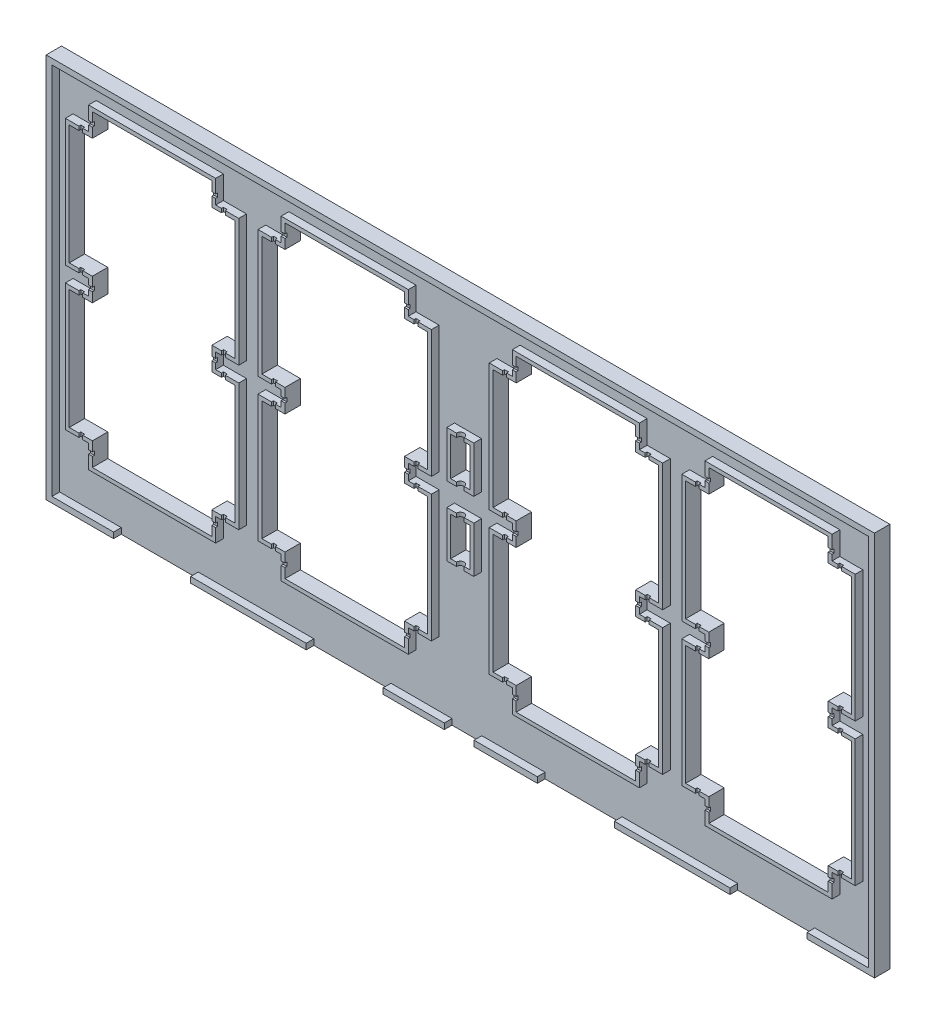
SolidWorks part; units mm, degrees
ref_plane "Спереди" through (0, 0, 0) normal (0, 0, 1) x (1, 0, 0)
ref_plane "Сверху" through (0, 0, 0) normal (0, 1, 0) x (1, 0, 0)
ref_plane "Справа" through (0, 0, 0) normal (1, 0, 0) x (0, 0, -1)
other "Configuration Table"
sketch "Эскиз1" plane through (0, 0, 0) normal (0, 0, 1) x (1, 0, 0)
  line L0 (0, 0) -> (210, 0)
  line L1 (210, 0) -> (210, 100)
  line L2 (210, 100) -> (0, 100)
  line L3 (0, 100) -> (0, 0)
  dimension "D1" = 210
  dimension "D2" = 100
extrude "Бобышка-Вытянуть1" add sketch "Эскиз1" along normal blind 2
sketch "Эскиз2" plane through (0, 0, 2) normal (0, 0, 1) x (1, 0, 0)
  line L4 (3.5, 56.2516) -> (9.5, 56.2516)
  line L5 (40.5, 87.2516) -> (46.5, 87.2516)
  line L6 (9.5, 56.2516) -> (9.5, 50.2516)
  line L7 (9.5, 93.2516) -> (9.5, 87.2516)
  line L9 (40.5, 87.2516) -> (40.5, 93.2516)
  line L10 (40.5, 93.2516) -> (9.5, 93.2516)
  line L11 (53.5, 56.2516) -> (59.5, 56.2516)
  line L12 (9.5, 19.2516) -> (9.5, 13.2516)
  line L13 (9.5, 13.2516) -> (40.5, 13.2516)
  line L14 (40.5, 13.2516) -> (40.5, 19.2516)
  line L16 (90.5, 87.2516) -> (96.5, 87.2516)
  line L20 (40.5, 56.2516) -> (40.5, 50.2516)
  line L21 (59.5, 56.2516) -> (59.5, 50.2516)
  line L22 (59.5, 93.2516) -> (59.5, 87.2516)
  line L23 (25, 93.2516) -> (25, 13.3713) construction
  line L24 (25, 56.2516) -> (25, 33.3628) construction
  line L25 (3.5, 50.2516) -> (3.5, 19.2516)
  line L26 (3.5, 19.2516) -> (9.5, 19.2516)
  line L28 (9.5, 50.2516) -> (3.5, 50.2516)
  line L30 (40.5, 56.2516) -> (46.5, 56.2516)
  line L31 (46.5, 56.2516) -> (46.5, 87.2516)
  line L33 (3.5, 87.2516) -> (3.5, 56.2516)
  line L36 (9.5, 87.2516) -> (3.5, 87.2516)
  line L38 (40.5, 19.2516) -> (46.5, 19.2516)
  line L39 (46.5, 19.2516) -> (46.5, 50.2516)
  line L40 (46.5, 50.2516) -> (40.5, 50.2516)
  line L41 (25, 19.2516) -> (25, 10.047) construction
  line L42 (6.5, 87.2516) -> (6.5, 54.1946) construction
  line L43 (0, 100) -> (0, 0) construction
  line L45 (90.5, 87.2516) -> (90.5, 93.2516)
  line L46 (90.5, 93.2516) -> (59.5, 93.2516)
  line L47 (59.5, 19.2516) -> (59.5, 13.2516)
  line L48 (59.5, 13.2516) -> (90.5, 13.2516)
  line L49 (90.5, 13.2516) -> (90.5, 19.2516)
  line L53 (90.5, 56.2516) -> (90.5, 50.2516)
  line L54 (53.5, 50.2516) -> (53.5, 19.2516)
  line L55 (53.5, 19.2516) -> (59.5, 19.2516)
  line L57 (59.5, 50.2516) -> (53.5, 50.2516)
  line L59 (90.5, 56.2516) -> (96.5, 56.2516)
  line L60 (96.5, 56.2516) -> (96.5, 87.2516)
  line L61 (53.5, 87.2516) -> (53.5, 56.2516)
  line L63 (59.5, 87.2516) -> (53.5, 87.2516)
  line L65 (90.5, 19.2516) -> (96.5, 19.2516)
  line L66 (96.5, 19.2516) -> (96.5, 50.2516)
  line L67 (96.5, 50.2516) -> (90.5, 50.2516)
  line L68 (75, 93.2516) -> (75, 13.3713) construction
  line L69 (75, 56.2516) -> (75, 33.3628) construction
  line L70 (75, 19.2516) -> (75, 10.047) construction
  line L71 (56.5, 87.2516) -> (56.5, 54.1946) construction
  line L72 (3.5, 56.2516) -> (9.5, 56.2516) construction
  line L73 (113.5, 56.2516) -> (119.5, 56.2516)
  line L74 (150.5, 87.2516) -> (156.5, 87.2516)
  line L75 (119.5, 56.2516) -> (119.5, 50.2516)
  line L76 (119.5, 93.2516) -> (119.5, 87.2516)
  line L78 (150.5, 87.2516) -> (150.5, 93.2516)
  line L79 (150.5, 93.2516) -> (119.5, 93.2516)
  line L80 (119.5, 19.2516) -> (119.5, 13.2516)
  line L81 (119.5, 13.2516) -> (150.5, 13.2516)
  line L82 (150.5, 13.2516) -> (150.5, 19.2516)
  line L86 (150.5, 56.2516) -> (150.5, 50.2516)
  line L87 (113.5, 50.2516) -> (113.5, 19.2516)
  line L88 (113.5, 19.2516) -> (119.5, 19.2516)
  line L90 (119.5, 50.2516) -> (113.5, 50.2516)
  line L92 (150.5, 56.2516) -> (156.5, 56.2516)
  line L93 (156.5, 56.2516) -> (156.5, 87.2516)
  line L94 (113.5, 87.2516) -> (113.5, 56.2516)
  line L96 (119.5, 87.2516) -> (113.5, 87.2516)
  line L98 (150.5, 19.2516) -> (156.5, 19.2516)
  line L99 (156.5, 19.2516) -> (156.5, 50.2516)
  line L100 (156.5, 50.2516) -> (150.5, 50.2516)
  line L101 (135, 93.2516) -> (135, 13.3713) construction
  line L102 (135, 56.2516) -> (135, 33.3628) construction
  line L103 (135, 19.2516) -> (135, 10.047) construction
  line L104 (116.5, 87.2516) -> (116.5, 54.1946) construction
  line L105 (90.5, 56.2516) -> (96.5, 56.2516) construction
  line L106 (53.5, 56.2516) -> (59.5, 56.2516) construction
  line L107 (163.5, 56.2516) -> (169.5, 56.2516)
  line L108 (200.5, 87.2516) -> (206.5, 87.2516)
  line L109 (169.5, 56.2516) -> (169.5, 50.2516)
  line L110 (169.5, 93.2516) -> (169.5, 87.2516)
  line L112 (200.5, 87.2516) -> (200.5, 93.2516)
  line L113 (200.5, 93.2516) -> (169.5, 93.2516)
  line L114 (169.5, 19.2516) -> (169.5, 13.2516)
  line L115 (169.5, 13.2516) -> (200.5, 13.2516)
  line L116 (200.5, 13.2516) -> (200.5, 19.2516)
  line L120 (200.5, 56.2516) -> (200.5, 50.2516)
  line L121 (163.5, 50.2516) -> (163.5, 19.2516)
  line L122 (163.5, 19.2516) -> (169.5, 19.2516)
  line L124 (169.5, 50.2516) -> (163.5, 50.2516)
  line L126 (200.5, 56.2516) -> (206.5, 56.2516)
  line L127 (206.5, 56.2516) -> (206.5, 87.2516)
  line L128 (163.5, 87.2516) -> (163.5, 56.2516)
  line L130 (169.5, 87.2516) -> (163.5, 87.2516)
  line L132 (200.5, 19.2516) -> (206.5, 19.2516)
  line L133 (206.5, 19.2516) -> (206.5, 50.2516)
  line L134 (206.5, 50.2516) -> (200.5, 50.2516)
  line L135 (185, 93.2516) -> (185, 13.3713) construction
  line L136 (185, 56.2516) -> (185, 33.3628) construction
  line L137 (185, 19.2516) -> (185, 10.047) construction
  line L138 (166.5, 87.2516) -> (166.5, 54.1946) construction
  line L139 (113.5, 56.2516) -> (119.5, 56.2516) construction
  line L140 (113.5, 56.2516) -> (119.5, 56.2516) construction
  line L141 (113.5, 56.2516) -> (119.5, 56.2516) construction
  line L142 (40.5, 56.2516) -> (46.5, 56.2516) construction
  line L143 (90.5, 56.2516) -> (96.5, 56.2516) construction
  line L144 (150.5, 56.2516) -> (156.5, 56.2516) construction
  line L145 (150.5, 56.2516) -> (156.5, 56.2516) construction
  line L146 (150.5, 56.2516) -> (156.5, 56.2516) construction
  dimension "D3" = 25
  dimension "D4" = 25
  dimension "D5" = 2
  dimension "D6" = 31
  dimension "D7" = 31
  dimension "D8" = 18.5
  dimension "D9" = 6
  dimension "D10" = 6
  dimension "D12" = 2
  dimension "D13" = 60
  dimension "D14" = 2
  dimension "D15" = 31
  dimension "D16" = 6
  dimension "D23" = 6
  dimension "D24" = 6
  dimension "D25" = 6
extrude "Вырез-Вытянуть1" cut sketch "Эскиз2" against normal blind 2 contours L11 L21 L57 L54 L55 L47 L48 L49 L65 L66 L67 L53 L59 L60 L16 L45 L46 L22 L63 L61 | L96 L94 L73 L75 L90 L87 L88 L80 L81 L82 L98 L99 L100 L86 L92 L93 L74 L78 L79 L76 | L12 L13 L14 L38 L39 L40 L20 L30 L31 L5 L9 L10 L7 L36 L33 L4 L6 L28 L25 L26 | L120 L126 L127 L108 L112 L113 L110 L130 L128 L107 L109 L124 L121 L122 L114 L115 L116 L132 L133 L134
sketch "Эскиз3" plane through (0, 0, 2) normal (0, 0, 1) x (1, 0, 0)
  line L0 (105, 100) -> (105, 0) construction
  line L1 (210, 100) -> (0, 100) construction
  line L2 (0, 0) -> (210, 0) construction
  line L3 (102.5, 67.2516) -> (107.5, 67.2516)
  line L4 (107.5, 67.2516) -> (107.5, 57.2516)
  line L5 (107.5, 57.2516) -> (102.5, 57.2516)
  line L6 (102.5, 57.2516) -> (102.5, 67.2516)
  line L7 (102.5, 49.2516) -> (102.5, 39.2516)
  line L8 (102.5, 39.2516) -> (107.5, 39.2516)
  line L10 (107.5, 49.2516) -> (102.5, 49.2516)
  line L11 (107.5, 49.2516) -> (107.5, 39.2516)
  line L13 (113.5, 56.2516) -> (119.5, 56.2516) construction
  point P14 (107.5, 62.2516)
  dimension "D1" = 10
  dimension "D2" = 5
  dimension "D3" = 5
  dimension "D4" = 10
  dimension "D5" = 2.5
  dimension "D6" = 8
  dimension "D7" = 1
extrude "Вырез-Вытянуть2" cut sketch "Эскиз3" against normal blind 2
sketch "Эскиз5" plane through (0, 0, 2) normal (0, 0, 1) x (1, 0, 0)
  line L0 (9.5, 93.2516) -> (40.5, 93.2516)
  line L1 (40.5, 93.2516) -> (40.5, 87.2516)
  line L2 (40.5, 87.2516) -> (46.5, 87.2516)
  line L3 (46.5, 87.2516) -> (46.5, 56.2516)
  line L4 (46.5, 56.2516) -> (40.5, 56.2516)
  line L5 (40.5, 56.2516) -> (40.5, 50.2516)
  line L6 (40.5, 50.2516) -> (46.5, 50.2516)
  line L7 (46.5, 50.2516) -> (46.5, 19.2516)
  line L8 (46.5, 19.2516) -> (40.5, 19.2516)
  line L9 (40.5, 19.2516) -> (40.5, 13.2516)
  line L10 (40.5, 13.2516) -> (9.5, 13.2516)
  line L11 (9.5, 13.2516) -> (9.5, 19.2516)
  line L12 (9.5, 19.2516) -> (3.5, 19.2516)
  line L13 (3.5, 19.2516) -> (3.5, 50.2516)
  line L14 (3.5, 50.2516) -> (9.5, 50.2516)
  line L15 (9.5, 50.2516) -> (9.5, 56.2516)
  line L16 (9.5, 56.2516) -> (3.5, 56.2516)
  line L17 (3.5, 56.2516) -> (3.5, 87.2516)
  line L18 (3.5, 87.2516) -> (9.5, 87.2516)
  line L19 (9.5, 87.2516) -> (9.5, 93.2516)
  line L20 (8.5, 88.2516) -> (8.5, 94.2516)
  line L21 (8.5, 94.2516) -> (41.5, 94.2516)
  line L22 (41.5, 94.2516) -> (41.5, 88.2516)
  line L23 (41.5, 88.2516) -> (47.5, 88.2516)
  line L24 (47.5, 88.2516) -> (47.5, 55.2516)
  line L25 (47.5, 55.2516) -> (41.5, 55.2516)
  line L26 (41.5, 55.2516) -> (41.5, 51.2516)
  line L27 (41.5, 51.2516) -> (47.5, 51.2516)
  line L28 (47.5, 51.2516) -> (47.5, 18.2516)
  line L29 (47.5, 18.2516) -> (41.5, 18.2516)
  line L30 (41.5, 18.2516) -> (41.5, 12.2516)
  line L31 (41.5, 12.2516) -> (8.5, 12.2516)
  line L32 (8.5, 12.2516) -> (8.5, 18.2516)
  line L33 (8.5, 18.2516) -> (2.5, 18.2516)
  line L34 (2.5, 18.2516) -> (2.5, 51.2516)
  line L35 (2.5, 51.2516) -> (8.5, 51.2516)
  line L36 (8.5, 51.2516) -> (8.5, 55.2516)
  line L37 (8.5, 55.2516) -> (2.5, 55.2516)
  line L38 (2.5, 55.2516) -> (2.5, 88.2516)
  line L39 (2.5, 88.2516) -> (8.5, 88.2516)
  dimension "D1" = 1
extrude "Бобышка-Вытянуть3" add sketch "Эскиз5" along normal blind 2
sketch "Эскиз6" plane through (0, 0, 2) normal (0, 0, 1) x (1, 0, 0)
  line L0 (59.5, 93.2516) -> (90.5, 93.2516)
  line L1 (90.5, 93.2516) -> (90.5, 87.2516)
  line L2 (90.5, 87.2516) -> (96.5, 87.2516)
  line L3 (96.5, 87.2516) -> (96.5, 56.2516)
  line L4 (96.5, 56.2516) -> (90.5, 56.2516)
  line L5 (90.5, 56.2516) -> (90.5, 50.2516)
  line L6 (90.5, 50.2516) -> (96.5, 50.2516)
  line L7 (96.5, 50.2516) -> (96.5, 19.2516)
  line L8 (96.5, 19.2516) -> (90.5, 19.2516)
  line L9 (90.5, 19.2516) -> (90.5, 13.2516)
  line L10 (90.5, 13.2516) -> (59.5, 13.2516)
  line L11 (59.5, 13.2516) -> (59.5, 19.2516)
  line L12 (59.5, 19.2516) -> (53.5, 19.2516)
  line L13 (53.5, 19.2516) -> (53.5, 50.2516)
  line L14 (53.5, 50.2516) -> (59.5, 50.2516)
  line L15 (59.5, 50.2516) -> (59.5, 56.2516)
  line L16 (53.5, 56.2516) -> (59.5, 56.2516) construction
  line L17 (59.5, 56.2516) -> (59.5, 50.2516) construction
  line L18 (59.5, 56.2516) -> (53.5, 56.2516)
  line L19 (53.5, 56.2516) -> (53.5, 87.2516)
  line L20 (53.5, 87.2516) -> (59.5, 87.2516)
  line L21 (59.5, 87.2516) -> (59.5, 93.2516)
  line L22 (58.5, 88.2516) -> (58.5, 94.2516)
  line L23 (58.5, 94.2516) -> (91.5, 94.2516)
  line L24 (91.5, 94.2516) -> (91.5, 88.2516)
  line L25 (91.5, 88.2516) -> (97.5, 88.2516)
  line L26 (97.5, 88.2516) -> (97.5, 55.2516)
  line L27 (97.5, 55.2516) -> (91.5, 55.2516)
  line L28 (91.5, 55.2516) -> (91.5, 51.2516)
  line L29 (91.5, 51.2516) -> (97.5, 51.2516)
  line L30 (97.5, 51.2516) -> (97.5, 18.2516)
  line L31 (97.5, 18.2516) -> (91.5, 18.2516)
  line L32 (91.5, 18.2516) -> (91.5, 12.2516)
  line L33 (91.5, 12.2516) -> (58.5, 12.2516)
  line L34 (58.5, 12.2516) -> (58.5, 18.2516)
  line L35 (58.5, 18.2516) -> (52.5, 18.2516)
  line L36 (52.5, 18.2516) -> (52.5, 51.2516)
  line L37 (52.5, 51.2516) -> (58.5, 51.2516)
  line L38 (58.5, 51.2516) -> (58.5, 55.2516)
  line L39 (58.5, 55.2516) -> (52.5, 55.2516)
  line L40 (52.5, 55.2516) -> (52.5, 88.2516)
  line L41 (52.5, 88.2516) -> (58.5, 88.2516)
  dimension "D1" = 1
extrude "Бобышка-Вытянуть4" add sketch "Эскиз6" along normal blind 2
sketch "Эскиз7" plane through (0, 0, 2) normal (0, 0, 1) x (1, 0, 0)
  line L0 (0, 100) -> (-2.5, 100)
  line L1 (-2.5, 100) -> (-2.5, 0)
  line L2 (-2.5, 0) -> (0, 0)
  line L3 (0, 0) -> (0, 100)
  dimension "D1" = 2.5
extrude "Бобышка-Вытянуть5" add sketch "Эскиз7" against normal blind 2
sketch "Эскиз8" plane through (0, 0, 2) normal (0, 0, 1) x (1, 0, 0)
  line L0 (210, 100) -> (212.5, 100)
  line L1 (212.5, 100) -> (212.5, 0)
  line L2 (212.5, 0) -> (210, 0)
  line L3 (210, 0) -> (210, 100)
  dimension "D1" = 2.5
extrude "Бобышка-Вытянуть6" add sketch "Эскиз8" against normal blind 2
sketch "Эскиз9" plane through (0, 0, 2) normal (0, 0, 1) x (1, 0, 0)
  line L0 (102.5, 67.2516) -> (107.5, 67.2516)
  line L1 (107.5, 67.2516) -> (107.5, 57.2516)
  line L2 (107.5, 57.2516) -> (102.5, 57.2516)
  line L3 (102.5, 57.2516) -> (102.5, 67.2516)
  line L4 (101.5, 56.2516) -> (101.5, 68.2516)
  line L5 (101.5, 68.2516) -> (108.5, 68.2516)
  line L6 (108.5, 68.2516) -> (108.5, 56.2516)
  line L7 (108.5, 56.2516) -> (101.5, 56.2516)
  dimension "D1" = 1
extrude "Бобышка-Вытянуть7" add sketch "Эскиз9" along normal blind 2
sketch "Эскиз10" plane through (0, 0, 2) normal (0, 0, 1) x (1, 0, 0)
  line L0 (102.5, 49.2516) -> (107.5, 49.2516)
  line L1 (107.5, 49.2516) -> (107.5, 39.2516)
  line L2 (107.5, 39.2516) -> (102.5, 39.2516)
  line L3 (102.5, 39.2516) -> (102.5, 49.2516)
  line L4 (101.5, 38.2516) -> (101.5, 50.2516)
  line L5 (101.5, 50.2516) -> (108.5, 50.2516)
  line L6 (108.5, 50.2516) -> (108.5, 38.2516)
  line L7 (108.5, 38.2516) -> (101.5, 38.2516)
  dimension "D1" = 1
extrude "Бобышка-Вытянуть8" add sketch "Эскиз10" along normal blind 2
sketch "Эскиз11" plane through (0, 0, 2) normal (0, 0, 1) x (1, 0, 0)
  line L0 (119.5, 93.2516) -> (150.5, 93.2516)
  line L1 (150.5, 93.2516) -> (150.5, 87.2516)
  line L2 (150.5, 87.2516) -> (156.5, 87.2516)
  line L3 (156.5, 87.2516) -> (156.5, 56.2516)
  line L4 (156.5, 56.2516) -> (150.5, 56.2516)
  line L5 (150.5, 56.2516) -> (150.5, 50.2516)
  line L6 (150.5, 50.2516) -> (156.5, 50.2516)
  line L7 (156.5, 50.2516) -> (156.5, 19.2516)
  line L8 (156.5, 19.2516) -> (150.5, 19.2516)
  line L9 (150.5, 19.2516) -> (150.5, 13.2516)
  line L10 (150.5, 13.2516) -> (119.5, 13.2516)
  line L11 (119.5, 13.2516) -> (119.5, 19.2516)
  line L12 (119.5, 19.2516) -> (113.5, 19.2516)
  line L13 (113.5, 19.2516) -> (113.5, 50.2516)
  line L14 (113.5, 50.2516) -> (119.5, 50.2516)
  line L15 (119.5, 50.2516) -> (119.5, 56.2516)
  line L16 (119.5, 56.2516) -> (113.5, 56.2516)
  line L17 (113.5, 56.2516) -> (113.5, 87.2516)
  line L18 (113.5, 87.2516) -> (119.5, 87.2516)
  line L19 (119.5, 87.2516) -> (119.5, 93.2516)
  line L20 (118.5, 88.2516) -> (118.5, 94.2516)
  line L21 (118.5, 94.2516) -> (151.5, 94.2516)
  line L22 (151.5, 94.2516) -> (151.5, 88.2516)
  line L23 (151.5, 88.2516) -> (157.5, 88.2516)
  line L24 (157.5, 88.2516) -> (157.5, 55.2516)
  line L25 (157.5, 55.2516) -> (151.5, 55.2516)
  line L26 (151.5, 55.2516) -> (151.5, 51.2516)
  line L27 (151.5, 51.2516) -> (157.5, 51.2516)
  line L28 (157.5, 51.2516) -> (157.5, 18.2516)
  line L29 (157.5, 18.2516) -> (151.5, 18.2516)
  line L30 (151.5, 18.2516) -> (151.5, 12.2516)
  line L31 (151.5, 12.2516) -> (118.5, 12.2516)
  line L32 (118.5, 12.2516) -> (118.5, 18.2516)
  line L33 (118.5, 18.2516) -> (112.5, 18.2516)
  line L34 (112.5, 18.2516) -> (112.5, 51.2516)
  line L35 (112.5, 51.2516) -> (118.5, 51.2516)
  line L36 (118.5, 51.2516) -> (118.5, 55.2516)
  line L37 (118.5, 55.2516) -> (112.5, 55.2516)
  line L38 (112.5, 55.2516) -> (112.5, 88.2516)
  line L39 (112.5, 88.2516) -> (118.5, 88.2516)
  dimension "D1" = 1
extrude "Бобышка-Вытянуть9" add sketch "Эскиз11" along normal blind 2
sketch "Эскиз12" plane through (0, 0, 2) normal (0, 0, 1) x (1, 0, 0)
  line L0 (169.5, 93.2516) -> (200.5, 93.2516)
  line L1 (200.5, 93.2516) -> (200.5, 87.2516)
  line L2 (200.5, 87.2516) -> (206.5, 87.2516)
  line L3 (206.5, 87.2516) -> (206.5, 56.2516)
  line L4 (206.5, 56.2516) -> (200.5, 56.2516)
  line L5 (200.5, 56.2516) -> (200.5, 50.2516)
  line L6 (200.5, 50.2516) -> (206.5, 50.2516)
  line L7 (206.5, 50.2516) -> (206.5, 19.2516)
  line L8 (206.5, 19.2516) -> (200.5, 19.2516)
  line L9 (200.5, 19.2516) -> (200.5, 13.2516)
  line L10 (200.5, 13.2516) -> (169.5, 13.2516)
  line L11 (169.5, 13.2516) -> (169.5, 19.2516)
  line L12 (169.5, 19.2516) -> (163.5, 19.2516)
  line L13 (163.5, 19.2516) -> (163.5, 50.2516)
  line L14 (163.5, 50.2516) -> (169.5, 50.2516)
  line L15 (169.5, 50.2516) -> (169.5, 56.2516)
  line L16 (163.5, 56.2516) -> (169.5, 56.2516) construction
  line L17 (169.5, 56.2516) -> (169.5, 50.2516) construction
  line L18 (169.5, 56.2516) -> (163.5, 56.2516)
  line L19 (163.5, 56.2516) -> (163.5, 87.2516)
  line L20 (163.5, 87.2516) -> (169.5, 87.2516)
  line L21 (169.5, 87.2516) -> (169.5, 93.2516)
  line L22 (168.5, 88.2516) -> (168.5, 94.2516)
  line L23 (168.5, 94.2516) -> (201.5, 94.2516)
  line L24 (201.5, 94.2516) -> (201.5, 88.2516)
  line L25 (201.5, 88.2516) -> (207.5, 88.2516)
  line L26 (207.5, 88.2516) -> (207.5, 55.2516)
  line L27 (207.5, 55.2516) -> (201.5, 55.2516)
  line L28 (201.5, 55.2516) -> (201.5, 51.2516)
  line L29 (201.5, 51.2516) -> (207.5, 51.2516)
  line L30 (207.5, 51.2516) -> (207.5, 18.2516)
  line L31 (207.5, 18.2516) -> (201.5, 18.2516)
  line L32 (201.5, 18.2516) -> (201.5, 12.2516)
  line L33 (201.5, 12.2516) -> (168.5, 12.2516)
  line L34 (168.5, 12.2516) -> (168.5, 18.2516)
  line L35 (168.5, 18.2516) -> (162.5, 18.2516)
  line L36 (162.5, 18.2516) -> (162.5, 51.2516)
  line L37 (162.5, 51.2516) -> (168.5, 51.2516)
  line L38 (168.5, 51.2516) -> (168.5, 55.2516)
  line L39 (168.5, 55.2516) -> (162.5, 55.2516)
  line L40 (162.5, 55.2516) -> (162.5, 88.2516)
  line L41 (162.5, 88.2516) -> (168.5, 88.2516)
  dimension "D1" = 1
extrude "Бобышка-Вытянуть10" add sketch "Эскиз12" along normal blind 2
sketch "Эскиз13" plane through (0, 0, 2) normal (0, 0, 1) x (1, 0, 0)
  line L0 (-1, 98.5) -> (211, 98.5)
  line L1 (-2.5, 100) -> (212.5, 100)
  line L2 (212.5, 100) -> (212.5, 0)
  line L3 (212.5, 0) -> (-2.5, 0)
  line L4 (-2.5, 0) -> (-2.5, 100)
  line L5 (211, 98.5) -> (211, 1.5)
  line L6 (211, 1.5) -> (-1, 1.5)
  line L7 (-1, 1.5) -> (-1, 98.5)
  dimension "D1" = 1.5
extrude "Бобышка-Вытянуть12" add sketch "Эскиз13" along normal blind 2
sketch "Эскиз15" plane through (0, 0, 4) normal (0, 0, 1) x (1, 0, 0)
  line L0 (6.5, 87.2516) -> (6.5, 19.2516) construction
  line L1 (9.5, 87.2516) -> (3.5, 87.2516) construction
  line L2 (3.5, 19.2516) -> (9.5, 19.2516) construction
  line L3 (7, 87.8467) -> (7, 16.4283)
  line L4 (7, 16.4283) -> (6, 16.4283)
  line L5 (6, 16.4283) -> (6, 89.7154)
  line L6 (6, 89.7154) -> (7, 89.7154)
  line L7 (7, 89.7154) -> (7, 87.8467)
  dimension "D1" = 0.5
  dimension "D2" = 0.5
extrude "Вырез-Вытянуть5" cut sketch "Эскиз15" against normal blind 0.5
sketch "Эскиз16" plane through (0, 0, 4) normal (0, 0, 1) x (1, 0, 0)
  line L0 (9.5, 53.2516) -> (202.9622, 53.2516) construction
  line L1 (9.5, 56.2516) -> (9.5, 50.2516) construction
  line L2 (9.5, 53.7516) -> (207.2357, 53.7516)
  line L3 (207.2357, 53.7516) -> (207.2357, 52.7516)
  line L4 (207.2357, 52.7516) -> (7.0331, 52.7516)
  line L5 (7.0331, 52.7516) -> (7.0331, 53.7516)
  line L6 (7.0331, 53.7516) -> (9.5, 53.7516)
  dimension "D1" = 0.5
  dimension "D2" = 0.5
extrude "Вырез-Вытянуть6" cut sketch "Эскиз16" against normal blind 0.5
sketch "Эскиз18" plane through (0, 38.2516, 0) normal (0, -1, 0) x (1, 0, 0)
  line L0 (-2.5, 4) -> (212.5, 4) construction
  circle A0 centre (105, 4) radius 1
extrude "Вырез-Вытянуть8" cut sketch "Эскиз18" against normal blind 40
sketch "Эскиз19" plane through (0, 0, 4) normal (0, 0, 1) x (1, 0, 0)
  line L0 (9.5, 16.2516) -> (200.5, 16.2516) construction
  line L1 (9.5, 19.2516) -> (9.5, 13.2516) construction
  line L2 (200.5, 13.2516) -> (200.5, 19.2516) construction
  line L3 (9.5, 16.7516) -> (205.6371, 16.7516)
  line L4 (205.6371, 16.7516) -> (205.6371, 15.7516)
  line L5 (205.6371, 15.7516) -> (6.3461, 15.7516)
  line L6 (6.3461, 15.7516) -> (6.3461, 16.7516)
  line L7 (6.3461, 16.7516) -> (9.5, 16.7516)
  dimension "D1" = 0.5
  dimension "D2" = 0.5
extrude "Вырез-Вытянуть9" cut sketch "Эскиз19" against normal blind 0.5
sketch "Эскиз20" plane through (0, 0, 4) normal (0, 0, 1) x (1, 0, 0)
  line L0 (9.5, 90.2516) -> (204.4151, 90.2516) construction
  line L1 (9.5, 93.2516) -> (9.5, 87.2516) construction
  line L2 (9.5, 90.7516) -> (205.9858, 90.7516)
  line L3 (205.9858, 90.7516) -> (205.9858, 89.7516)
  line L4 (205.9858, 89.7516) -> (6.902, 89.7516)
  line L5 (6.902, 89.7516) -> (6.902, 90.7516)
  line L6 (6.902, 90.7516) -> (9.5, 90.7516)
  dimension "D1" = 0.5
  dimension "D2" = 0.5
extrude "Вырез-Вытянуть10" cut sketch "Эскиз20" against normal blind 0.5
sketch "Эскиз21" plane through (0, 0, 4) normal (0, 0, 1) x (1, 0, 0)
  line L0 (43.5, 19.2516) -> (43.5, 87.2516) construction
  line L1 (40.5, 19.2516) -> (46.5, 19.2516) construction
  line L2 (46.5, 87.2516) -> (40.5, 87.2516) construction
  line L3 (44, 87.2516) -> (44, 14.6693)
  line L4 (44, 14.6693) -> (43, 14.6693)
  line L5 (43, 14.6693) -> (43, 89.404)
  line L6 (43, 89.404) -> (44, 89.404)
  line L7 (44, 89.404) -> (44, 87.2516)
  dimension "D1" = 0.5
  dimension "D2" = 0.5
extrude "Вырез-Вытянуть11" cut sketch "Эскиз21" against normal blind 0.5
sketch "Эскиз22" plane through (0, 0, 4) normal (0, 0, 1) x (1, 0, 0)
  line L0 (56.5, 87.2516) -> (56.5, 19.2516) construction
  line L1 (59.5, 87.2516) -> (53.5, 87.2516) construction
  line L2 (53.5, 19.2516) -> (59.5, 19.2516) construction
  line L3 (57, 87.2516) -> (57, 16.867)
  line L4 (57, 16.867) -> (56, 16.867)
  line L5 (56, 16.867) -> (56, 91.2358)
  line L6 (56, 91.2358) -> (57, 91.2358)
  line L7 (57, 91.2358) -> (57, 87.2516)
  dimension "D1" = 0.5
  dimension "D2" = 0.5
extrude "Вырез-Вытянуть12" cut sketch "Эскиз22" against normal blind 0.5
sketch "Эскиз23" plane through (0, 0, 4) normal (0, 0, 1) x (1, 0, 0)
  line L0 (93.5, 87.2516) -> (93.5, 19.2516) construction
  line L1 (96.5, 87.2516) -> (90.5, 87.2516) construction
  line L2 (90.5, 19.2516) -> (96.5, 19.2516) construction
  line L3 (94, 19.2516) -> (94, 90.8274)
  line L4 (94, 90.8274) -> (93, 90.8274)
  line L5 (93, 90.8274) -> (93, 16.2231)
  line L6 (93, 16.2231) -> (94, 16.2231)
  line L7 (94, 16.2231) -> (94, 19.2516)
  dimension "D1" = 0.5
  dimension "D2" = 0.5
extrude "Вырез-Вытянуть13" cut sketch "Эскиз23" against normal blind 0.5
sketch "Эскиз24" plane through (0, 0, 4) normal (0, 0, 1) x (1, 0, 0)
  line L0 (116.5, 87.2516) -> (116.5, 19.2516) construction
  line L1 (119.5, 87.2516) -> (113.5, 87.2516) construction
  line L2 (113.5, 19.2516) -> (119.5, 19.2516) construction
  line L3 (116, 19.2516) -> (116, 17.2818)
  line L4 (116, 17.2818) -> (117, 17.2818)
  line L5 (117, 17.2818) -> (117, 91.1115)
  line L6 (117, 91.1115) -> (116, 91.1115)
  line L7 (116, 91.1115) -> (116, 19.2516)
  dimension "D1" = 0.5
  dimension "D2" = 0.5
extrude "Вырез-Вытянуть14" cut sketch "Эскиз24" against normal blind 0.5
sketch "Эскиз25" plane through (0, 0, 4) normal (0, 0, 1) x (1, 0, 0)
  line L0 (153.5, 87.2516) -> (153.5, 19.2516) construction
  line L1 (156.5, 87.2516) -> (150.5, 87.2516) construction
  line L2 (150.5, 19.2516) -> (156.5, 19.2516) construction
  line L3 (154, 19.2516) -> (154, 16.4787)
  line L4 (154, 16.4787) -> (153, 16.4787)
  line L5 (153, 16.4787) -> (153, 93.5281)
  line L7 (153, 93.5281) -> (154, 93.5281)
  line L8 (154, 93.5281) -> (154, 19.2516)
  dimension "D1" = 0.5
  dimension "D2" = 0.5
extrude "Вырез-Вытянуть15" cut sketch "Эскиз25" against normal blind 0.5
sketch "Эскиз26" plane through (0, 0, 4) normal (0, 0, 1) x (1, 0, 0)
  line L0 (166.5, 19.2516) -> (166.5, 87.2516) construction
  line L1 (163.5, 19.2516) -> (169.5, 19.2516) construction
  line L2 (169.5, 87.2516) -> (163.5, 87.2516) construction
  line L3 (167, 87.2516) -> (167, 89.7461)
  line L4 (167, 89.7461) -> (166, 89.7461)
  line L5 (166, 89.7461) -> (166, 15.4759)
  line L6 (166, 15.4759) -> (167, 15.4759)
  line L7 (167, 15.4759) -> (167, 87.2516)
  dimension "D1" = 0.5
  dimension "D2" = 0.5
extrude "Вырез-Вытянуть16" cut sketch "Эскиз26" against normal blind 0.5
sketch "Эскиз27" plane through (0, 0, 4) normal (0, 0, 1) x (1, 0, 0)
  line L0 (203.5, 87.2516) -> (203.5, 19.2516) construction
  line L1 (206.5, 87.2516) -> (200.5, 87.2516) construction
  line L2 (200.5, 19.2516) -> (206.5, 19.2516) construction
  line L3 (204, 19.2516) -> (204, 15.5041)
  line L4 (204, 15.5041) -> (203, 15.5041)
  line L5 (203, 15.5041) -> (203, 91.2528)
  line L6 (203, 91.2528) -> (204, 91.2528)
  line L7 (204, 91.2528) -> (204, 19.2516)
  dimension "D1" = 0.5
  dimension "D2" = 0.5
extrude "Вырез-Вытянуть17" cut sketch "Эскиз27" against normal blind 0.5
sketch "Эскиз28" plane through (0, 0, 2) normal (0, 0, 1) x (1, 0, 0)
  line L0 (15, 3.5631) -> (15, -1.5784)
  line L1 (15, -1.5784) -> (35, -1.5784)
  line L2 (35, -1.5784) -> (35, 3.5631)
  line L3 (35, 3.5631) -> (15, 3.5631)
  line L4 (25, 12.2516) -> (25, 24.8241) construction
  line L5 (8.5, 12.2516) -> (41.5, 12.2516) construction
  line L6 (65, 3.5631) -> (65, -1.5784)
  line L7 (65, -1.5784) -> (85, -1.5784)
  line L8 (85, -1.5784) -> (85, 3.5631)
  line L9 (85, 3.5631) -> (65, 3.5631)
  line L10 (15, 3.5631) -> (65, 3.5631) construction
  line L11 (125, 3.5631) -> (125, -1.5784)
  line L12 (125, -1.5784) -> (145, -1.5784)
  line L13 (145, -1.5784) -> (145, 3.5631)
  line L14 (145, 3.5631) -> (125, 3.5631)
  line L15 (65, 3.5631) -> (125, 3.5631) construction
  line L16 (175, 3.5631) -> (175, -1.5784)
  line L17 (175, -1.5784) -> (195, -1.5784)
  line L18 (195, -1.5784) -> (195, 3.5631)
  line L19 (195, 3.5631) -> (175, 3.5631)
  line L20 (125, 3.5631) -> (175, 3.5631) construction
  point P8 (15, 0.9923)
  dimension "D1" = 20
  dimension "D2" = 10
  dimension "D4" = 50
  dimension "D6" = 60
  dimension "D8" = 50
  dimension "D3" = 2
  dimension "D5" = 2
  dimension "D7" = 2
extrude "Вырез-Вытянуть18" cut sketch "Эскиз28" along normal blind 2
sketch "Эскиз29" plane through (0, 0, 2) normal (0, 0, 1) x (1, 0, 0)
  line L0 (100.8505, 3.1793) -> (100.8505, -1.589)
  line L1 (100.8505, -1.589) -> (108.5858, -1.589)
  line L2 (108.5858, -1.589) -> (108.5858, 3.1793)
  line L3 (108.5858, 3.1793) -> (100.8505, 3.1793)
extrude "Вырез-Вытянуть19" cut sketch "Эскиз29" along normal blind 2
